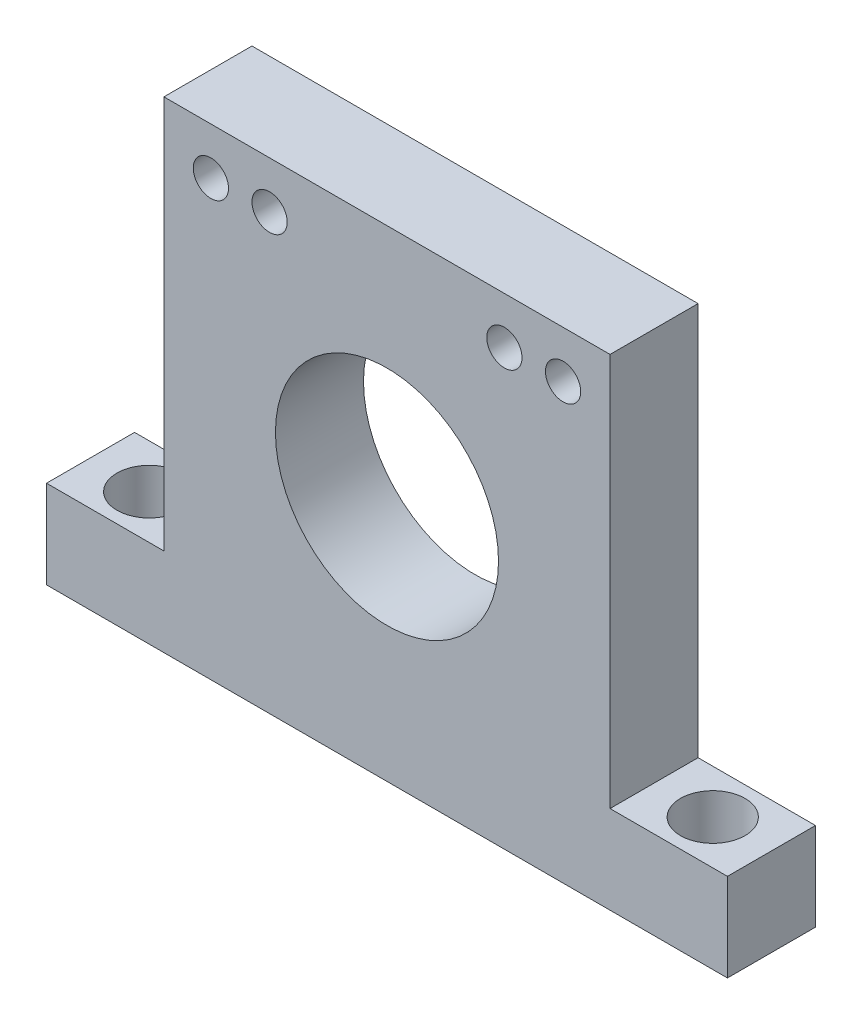
SolidWorks part; units mm, degrees
material "6061-T6 (SS)"
ref_plane "Frontal Plane" through (0, 0, 0) normal (0, 0, 1) x (1, 0, 0)
ref_plane "Horizontal Plane" through (0, 0, 0) normal (0, 1, 0) x (1, 0, 0)
ref_plane "Profile Plane" through (0, 0, 0) normal (1, 0, 0) x (0, 0, -1)
sketch "Sketch1" plane through (0, 0, 0) normal (0, 0, 1) x (1, 0, 0)
  line L0 (-29, 0) -> (29, 0)
  line L1 (29, 0) -> (29, 7.5)
  line L2 (29, 7.5) -> (19, 7.5)
  line L3 (19, 7.5) -> (19, 41)
  line L4 (19, 41) -> (-19, 41)
  line L5 (-19, 41) -> (-19, 7.5)
  line L6 (-19, 7.5) -> (-29, 7.5)
  line L7 (-29, 7.5) -> (-29, 0)
  circle A0 centre (0, 21) radius 9.5
  point P4 (0, 0)
  dimension "D6" = 19
  dimension "D1" = 7.5
  dimension "D2" = 10
  dimension "D3" = 21
  dimension "D4" = 20
  dimension "D5" = 38
extrude "Boss-Extrude1" add sketch "Sketch1" against normal blind 7.5
sketch "Sketch2" plane through (0, 0, 0) normal (0, 0, 1) x (1, 0, 0)
  line L0 (-29, 21) -> (29, 21) construction
  line L1 (19, 7.5) -> (19, 41) construction
  line L3 (19, 41) -> (-19, 41) construction
  line L4 (29, 0) -> (29, 7.5) construction
  line L5 (0, 0) -> (0, 79.9514) construction
  circle A0 centre (10, 37) radius 1.5
  circle A1 centre (15, 37) radius 1.5
  circle A4 centre (-15, 37) radius 1.5
  circle A5 centre (-10, 37) radius 1.5
  dimension "D4" = 3
  dimension "D1" = 4
  dimension "D2" = 4
  dimension "D5" = 5
extrude "Cut-Extrude2" cut sketch "Sketch2" against normal through all
sketch "Sketch3" plane through (0, 7.5, 0) normal (0, 1, 0) x (1, 0, 0)
  line L0 (-29, 7.5) -> (-29, 0) construction
  line L1 (29, 7.5) -> (29, 0) construction
  circle A0 centre (-24, 3.75) radius 2.75
  circle A1 centre (24, 3.75) radius 2.75
  point P7 (-29, 3.75)
  dimension "D1" = 5.5
  dimension "D2" = 5
  dimension "D3" = 5
extrude "Cut-Extrude3" cut sketch "Sketch3" against normal through all
equation "\"BaseL\"= 6ft"
equation "\"BaseW\"= 5.5in"
equation "\"BaseThickness\"= 1in"
equation "\"RailGap\"= 4cm"
equation "\"SlidePlateL\"= 8cm"
equation "\"SlidePlateW\"= 11cm"
equation "\"SlidePlateThickness\"= 5mm"
equation "\"SlidePlateClearance\"= 1cm"
equation "\"BoxThickness\"= .5cm"
equation "\"BoxX\"= \"RailGap\" + 30mm"
equation "\"BoxH\"= 2cm + \"SlidePlateClearance\" + \"SlidePlateThickness\" + 3cm"
equation "\"PulleyRadius\"= 15.1mm"
equation "\"PulleyH\"= 30mm + 21.4056mm - 2.5mm"
equation "\"PulleyShaftDiameter\"= .3125in"
equation "\"PulleyShaftL\"= 4in"
equation "\"PulleyShaft2L\"= 3in"
equation "\"MotorL\"= 4.43in"
equation "\"MotorRadius\"= 1.291in"
equation "\"MotorShaftRadius\"= .15625in"
equation "\"MotorShaftL\"= 1.75in"
equation "\"HeadstoneThickness\"= 7.5mm"
equation "\"BeltL\"= 1500mm + \"80\""
equation "\"BeltThickness\"= 2.5mm"
equation "\"BeltW\"= .375in"
equation "\"BeltLockH\"= \"PulleyH\" + 19.4056mm - (\"SlidePlateThickness\" + \"SlidePlateClearance\" + 15mm + 5mm)"
equation "\"EncoderL\"= 33mm"
equation "\"EncoderRadius\"= 19mm"
equation "\"EncoderShaftRadius\"= 3mm"
equation "\"EncoderShaftL\"= 15mm"
equation "\"PendulumShaftL\"= \"100mm\" "
equation "\"PendulumShaftRadius\"= 3mm"
equation "\"RodL\"= 39in"
equation "\"RodRadius\"= 3mm"
equation "\"PillowBlockCenterH\"= \"EncoderRadius\" + 2mm"
equation "\"D1@Sketch1\"=\"HeadstoneThickness\""
equation "\"D3@Sketch1\"=\"PillowBlockCenterH\""
equation "\"D5@Sketch1\"=\"EncoderRadius\"*2"
